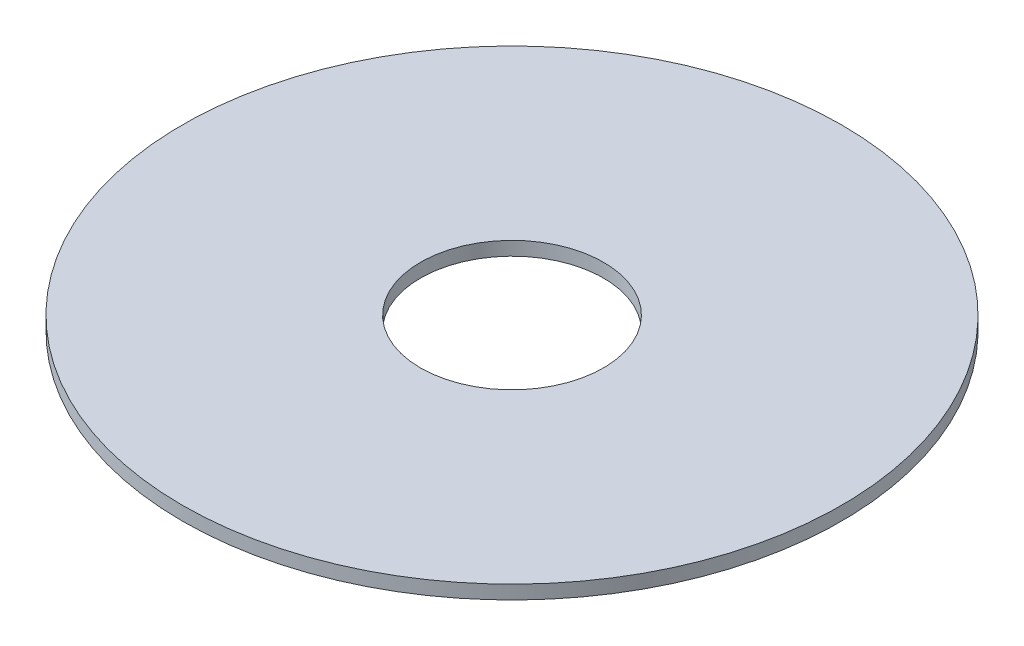
SolidWorks part; units mm, degrees
ref_plane "Front Plane" through (0, 0, 0) normal (0, 0, 1) x (1, 0, 0)
ref_plane "Top Plane" through (0, 0, 0) normal (0, 1, 0) x (1, 0, 0)
ref_plane "Right Plane" through (0, 0, 0) normal (1, 0, 0) x (0, 0, -1)
sketch "Sketch2" plane through (0, 0, 0) normal (0, 1, 0) x (1, 0, 0)
  circle A0 centre (0, 0) radius 18
  circle A1 centre (0, 0) radius 5
extrude "Boss-Extrude1" add sketch "Sketch2" along normal blind 0.75
